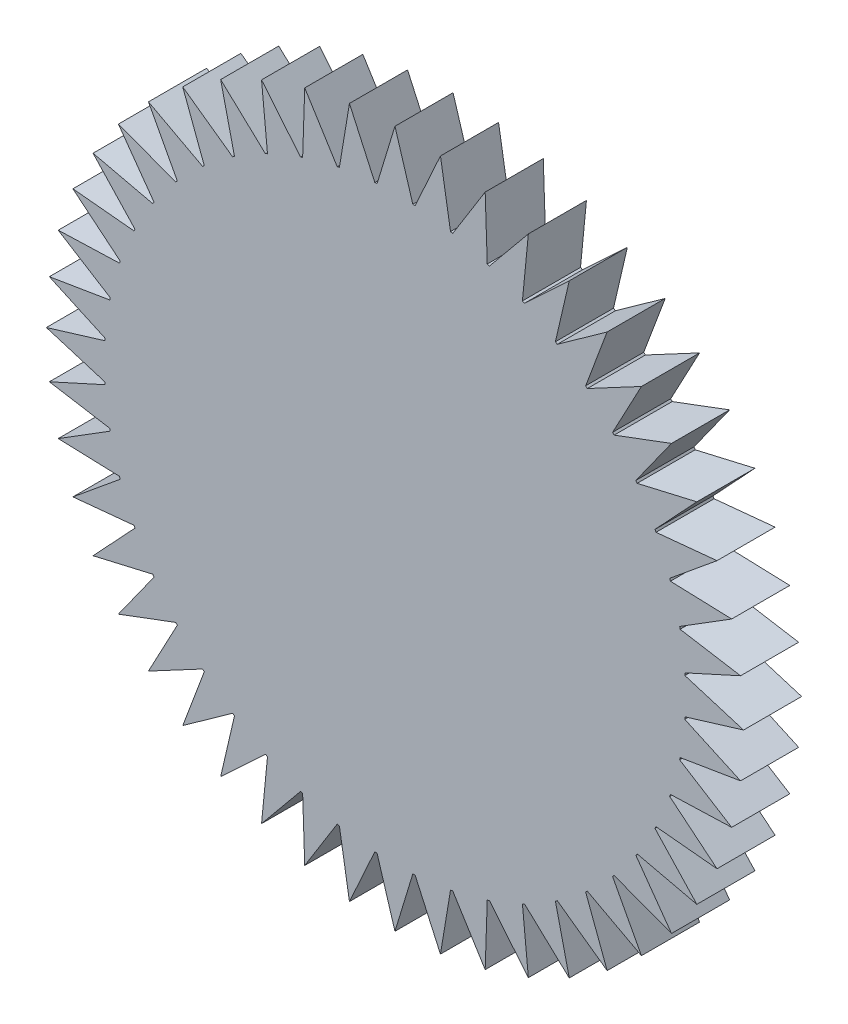
SolidWorks part; units mm, degrees
ref_plane "Plan de face" through (0, 0, 0) normal (0, 0, 1) x (1, 0, 0)
ref_plane "Plan de dessus" through (0, 0, 0) normal (0, 1, 0) x (1, 0, 0)
ref_plane "Plan de droite" through (0, 0, 0) normal (1, 0, 0) x (0, 0, -1)
sketch "Esquisse1" plane through (0, 0, 0) normal (0, 0, 1) x (1, 0, 0)
  circle A0 centre (0, 0) radius 30
  dimension "D1" = 60
extrude "Boss.-Extru.1" add sketch "Esquisse1" along normal blind 5
sketch "Esquisse3" plane through (0, 0, 5) normal (0, 0, 1) x (1, 0, 0)
  line L0 (0, 30) -> (0, 20.5682) construction
  line L1 (0, 30) -> (-1.5376, 24.9527)
  line L2 (0, 30) -> (1.5376, 24.9527)
  line L3 (3.9158, 29.7433) -> (1.7325, 24.9399)
  line L4 (3.9158, 29.7433) -> (4.7814, 24.5385)
  line L5 (7.7646, 28.9778) -> (4.973, 24.5004)
  line L6 (7.7646, 28.9778) -> (7.9434, 23.7045)
  line L7 (11.4805, 27.7164) -> (8.1284, 23.6417)
  line L8 (11.4805, 27.7164) -> (10.9695, 22.4648)
  line L9 (15, 25.9808) -> (11.1447, 22.3785)
  line L10 (15, 25.9808) -> (13.8079, 20.8408)
  line L11 (18.2628, 23.8006) -> (13.9704, 20.7323)
  line L12 (18.2628, 23.8006) -> (16.4101, 18.8602)
  line L13 (21.2132, 21.2132) -> (16.5569, 18.7315)
  line L14 (21.2132, 21.2132) -> (18.7315, 16.5569)
  line L15 (23.8006, 18.2628) -> (18.8602, 16.4101)
  line L16 (23.8006, 18.2628) -> (20.7323, 13.9704)
  line L17 (25.9808, 15) -> (20.8408, 13.8079)
  line L18 (25.9808, 15) -> (22.3785, 11.1447)
  line L19 (27.7164, 11.4805) -> (22.4648, 10.9695)
  line L20 (27.7164, 11.4805) -> (23.6417, 8.1284)
  line L21 (28.9778, 7.7646) -> (23.7045, 7.9434)
  line L22 (28.9778, 7.7646) -> (24.5004, 4.973)
  line L23 (29.7433, 3.9158) -> (24.5385, 4.7814)
  line L24 (29.7433, 3.9158) -> (24.9399, 1.7325)
  line L25 (30, 0) -> (24.9527, 1.5376)
  line L26 (30, 0) -> (24.9527, -1.5376)
  line L27 (29.7433, -3.9158) -> (24.9399, -1.7325)
  line L28 (29.7433, -3.9158) -> (24.5385, -4.7814)
  line L29 (28.9778, -7.7646) -> (24.5004, -4.973)
  line L30 (28.9778, -7.7646) -> (23.7045, -7.9434)
  line L31 (27.7164, -11.4805) -> (23.6417, -8.1284)
  line L32 (27.7164, -11.4805) -> (22.4648, -10.9695)
  line L33 (25.9808, -15) -> (22.3785, -11.1447)
  line L34 (25.9808, -15) -> (20.8408, -13.8079)
  line L35 (23.8006, -18.2628) -> (20.7323, -13.9704)
  line L36 (23.8006, -18.2628) -> (18.8602, -16.4101)
  line L37 (21.2132, -21.2132) -> (18.7315, -16.5569)
  line L38 (21.2132, -21.2132) -> (16.5569, -18.7315)
  line L39 (18.2628, -23.8006) -> (16.4101, -18.8602)
  line L40 (18.2628, -23.8006) -> (13.9704, -20.7323)
  line L41 (15, -25.9808) -> (13.8079, -20.8408)
  line L42 (15, -25.9808) -> (11.1447, -22.3785)
  line L43 (11.4805, -27.7164) -> (10.9695, -22.4648)
  line L44 (11.4805, -27.7164) -> (8.1284, -23.6417)
  line L45 (7.7646, -28.9778) -> (7.9434, -23.7045)
  line L46 (7.7646, -28.9778) -> (4.973, -24.5004)
  line L47 (3.9158, -29.7433) -> (4.7814, -24.5385)
  line L48 (3.9158, -29.7433) -> (1.7325, -24.9399)
  line L49 (0, -30) -> (1.5376, -24.9527)
  line L50 (0, -30) -> (-1.5376, -24.9527)
  line L51 (-3.9158, -29.7433) -> (-1.7325, -24.9399)
  line L52 (-3.9158, -29.7433) -> (-4.7814, -24.5385)
  line L53 (-7.7646, -28.9778) -> (-4.973, -24.5004)
  line L54 (-7.7646, -28.9778) -> (-7.9434, -23.7045)
  line L55 (-11.4805, -27.7164) -> (-8.1284, -23.6417)
  line L56 (-11.4805, -27.7164) -> (-10.9695, -22.4648)
  line L57 (-15, -25.9808) -> (-11.1447, -22.3785)
  line L58 (-15, -25.9808) -> (-13.8079, -20.8408)
  line L59 (-18.2628, -23.8006) -> (-13.9704, -20.7323)
  line L60 (-18.2628, -23.8006) -> (-16.4101, -18.8602)
  line L61 (-21.2132, -21.2132) -> (-16.5569, -18.7315)
  line L62 (-21.2132, -21.2132) -> (-18.7315, -16.5569)
  line L63 (-23.8006, -18.2628) -> (-18.8602, -16.4101)
  line L64 (-23.8006, -18.2628) -> (-20.7323, -13.9704)
  line L65 (-25.9808, -15) -> (-20.8408, -13.8079)
  line L66 (-25.9808, -15) -> (-22.3785, -11.1447)
  line L67 (-27.7164, -11.4805) -> (-22.4648, -10.9695)
  line L68 (-27.7164, -11.4805) -> (-23.6417, -8.1284)
  line L69 (-28.9778, -7.7646) -> (-23.7045, -7.9434)
  line L70 (-28.9778, -7.7646) -> (-24.5004, -4.973)
  line L71 (-29.7433, -3.9158) -> (-24.5385, -4.7814)
  line L72 (-29.7433, -3.9158) -> (-24.9399, -1.7325)
  line L73 (-30, 0) -> (-24.9527, -1.5376)
  line L74 (-30, 0) -> (-24.9527, 1.5376)
  line L75 (-29.7433, 3.9158) -> (-24.9399, 1.7325)
  line L76 (-29.7433, 3.9158) -> (-24.5385, 4.7814)
  line L77 (-28.9778, 7.7646) -> (-24.5004, 4.973)
  line L78 (-28.9778, 7.7646) -> (-23.7045, 7.9434)
  line L79 (-27.7164, 11.4805) -> (-23.6417, 8.1284)
  line L80 (-27.7164, 11.4805) -> (-22.4648, 10.9695)
  line L81 (-25.9808, 15) -> (-22.3785, 11.1447)
  line L82 (-25.9808, 15) -> (-20.8408, 13.8079)
  line L83 (-23.8006, 18.2628) -> (-20.7323, 13.9704)
  line L84 (-23.8006, 18.2628) -> (-18.8602, 16.4101)
  line L85 (-21.2132, 21.2132) -> (-18.7315, 16.5569)
  line L86 (-21.2132, 21.2132) -> (-16.5569, 18.7315)
  line L87 (-18.2628, 23.8006) -> (-16.4101, 18.8602)
  line L88 (-18.2628, 23.8006) -> (-13.9704, 20.7323)
  line L89 (-15, 25.9808) -> (-13.8079, 20.8408)
  line L90 (-15, 25.9808) -> (-11.1447, 22.3785)
  line L91 (-11.4805, 27.7164) -> (-10.9695, 22.4648)
  line L92 (-11.4805, 27.7164) -> (-8.1284, 23.6417)
  line L93 (-7.7646, 28.9778) -> (-7.9434, 23.7045)
  line L94 (-7.7646, 28.9778) -> (-4.973, 24.5004)
  line L95 (-3.9158, 29.7433) -> (-4.7814, 24.5385)
  line L96 (-3.9158, 29.7433) -> (-1.7325, 24.9399)
  circle A0 centre (0, 0) radius 25
  circle A1 centre (0, 0) radius 30 construction
  point P10 (0, 0)
  point P11 (0, 0)
  point P154 (0, 0)
  circle M3 centre (0, 0) radius 30
  dimension "D1" = 50
  dimension "D2" = 5.2763
  dimension "D3" = 48
extrude "Enlèv. mat.-Extru.1" cut sketch "Esquisse3" against normal blind 5 contours A0 L89 L88 M3 | A0 L87 L86 M3 | A0 L85 L84 M3 | A0 L83 L82 M3 | A0 L81 L80 M3 | A0 L79 L78 M3 | A0 L77 L76 M3 | A0 L75 L74 M3 | A0 L73 L72 M3 | A0 L71 L70 M3 | A0 L69 L68 M3 | A0 L67 L66 M3 | A0 L65 L64 M3 | A0 L63 L62 M3 | A0 L61 L60 M3 | A0 L59 L58 M3 | A0 L57 L56 M3 | A0 L55 L54 M3 | A0 L53 L52 M3 | A0 L51 L50 M3 | A0 L49 L48 M3 | A0 L47 L46 M3 | A0 L45 L44 M3 | A0 L43 L42 M3 | A0 L41 L40 M3 | A0 L39 L38 M3 | A0 L37 L36 M3 | A0 L35 L34 M3 | A0 L33 L32 M3 | A0 L31 L30 M3 | A0 L29 L28 M3 | A0 L27 L26 M3 | A0 L25 L24 M3 | A0 L23 L22 M3 | A0 L21 L20 M3 | A0 L19 L18 M3 | A0 L17 L16 M3 | A0 L15 L14 M3 | A0 L13 L12 M3 | A0 L11 L10 M3 | A0 L9 L8 M3 | A0 L7 L6 M3 | A0 L91 L90 M3 | A0 L93 L92 M3 | A0 L95 L94 M3 | A0 L1 L96 M3 | A0 L3 L2 M3 | A0 L5 L4 M3
